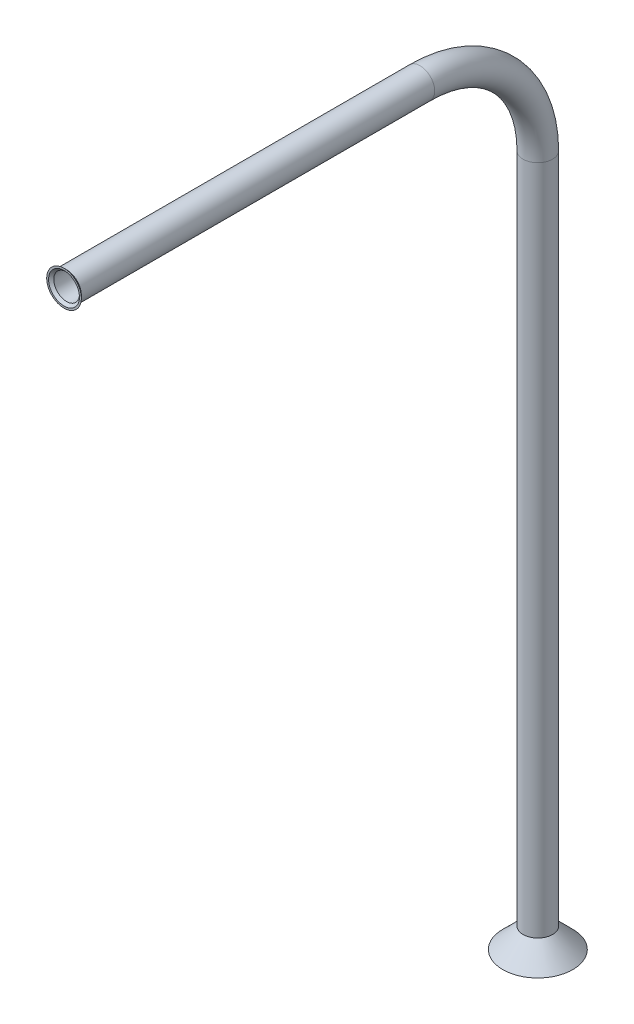
SolidWorks part; units mm, degrees
material "Brass"
ref_plane "Front Plane" through (0, 0, 0) normal (0, 0, 1) x (1, 0, 0)
ref_plane "Top Plane" through (0, 0, 0) normal (0, 1, 0) x (1, 0, 0)
ref_plane "Right Plane" through (0, 0, 0) normal (1, 0, 0) x (0, 0, -1)
sketch "Sketch1" plane through (0, 0, 0) normal (0, 0, 1) x (1, 0, 0)
  circle A0 centre (0, 0) radius 6.35
  circle A1 centre (0, 0) radius 5.5372
  dimension "D1" = 12.7
  dimension "D2" = 0.8128
sketch "Sketch2" plane through (0, 0, 0) normal (1, 0, 0) x (0, 0, -1)
  line L0 (0, 0) -> (152.4, 0)
  line L1 (203.2, -50.8) -> (203.2, -340.36)
  arc A0 (152.4, 0) -> (203.2, -50.8) centre (152.4, -50.8) cw
  point P6 (203.2, 0)
  dimension "D3" = 50.8
  dimension "D1" = 203.2
  dimension "D2" = 340.36
sweep "Sweep1" add profiles "Sketch1" path "Sketch2"
sketch "Sketch3" plane through (0, 0, 0) normal (1, 0, 0) x (0, 0, -1)
  line L0 (0, -28.0775) -> (0, 28.0775) construction
  line L1 (-5.7906, 5.5372) -> (5.7906, 5.5372) construction
  line L2 (0, 5.5372) -> (-1.1225, 6.6597)
  line L3 (10.1293, 0) -> (-10.1293, 0) construction
  line L4 (-3.5626, 6.35) -> (3.5626, 6.35) construction
  line L5 (0, 6.35) -> (-1.1225, 7.4725)
  line L6 (-1.1225, 7.4725) -> (-1.1225, 6.6597)
  line L7 (0, 6.35) -> (0, 5.5372)
  point P4 (0, 0)
  point P7 (0, 5.5372)
  point P11 (0, 0)
  point P15 (0, 6.35)
  dimension "D2" = 45
  dimension "D1" = 5.5372
  dimension "D3" = 6.35
  dimension "D4" = 45
revolve "Revolve1" add sketch "Sketch3" angle 360 about L3
sketch "Sketch4" plane through (0, 0, 0) normal (1, 0, 0) x (0, 0, -1)
  line L0 (133.0405, -340.36) -> (273.3595, -340.36) construction
  line L2 (203.2, -309.2613) -> (203.2, -371.4587) construction
  line L3 (196.85, -349.0069) -> (196.85, -331.7131) construction
  line L4 (197.6628, -339.5298) -> (197.6628, -341.1902) construction
  line L5 (196.85, -340.36) -> (188.1075, -349.1025)
  line L6 (197.6628, -340.36) -> (188.9203, -349.1025)
  line L7 (188.1075, -349.1025) -> (188.9203, -349.1025)
  line L8 (196.85, -340.36) -> (197.6628, -340.36)
  point P4 (203.2, -340.36)
  point P8 (203.2, -340.36)
  point P11 (196.85, -340.36)
  point P14 (197.6628, -340.36)
  dimension "D1" = 6.35
  dimension "D2" = 5.5372
  dimension "D3" = 45
  dimension "D4" = 45
revolve "Revolve2" add sketch "Sketch4" angle 360 about L2
